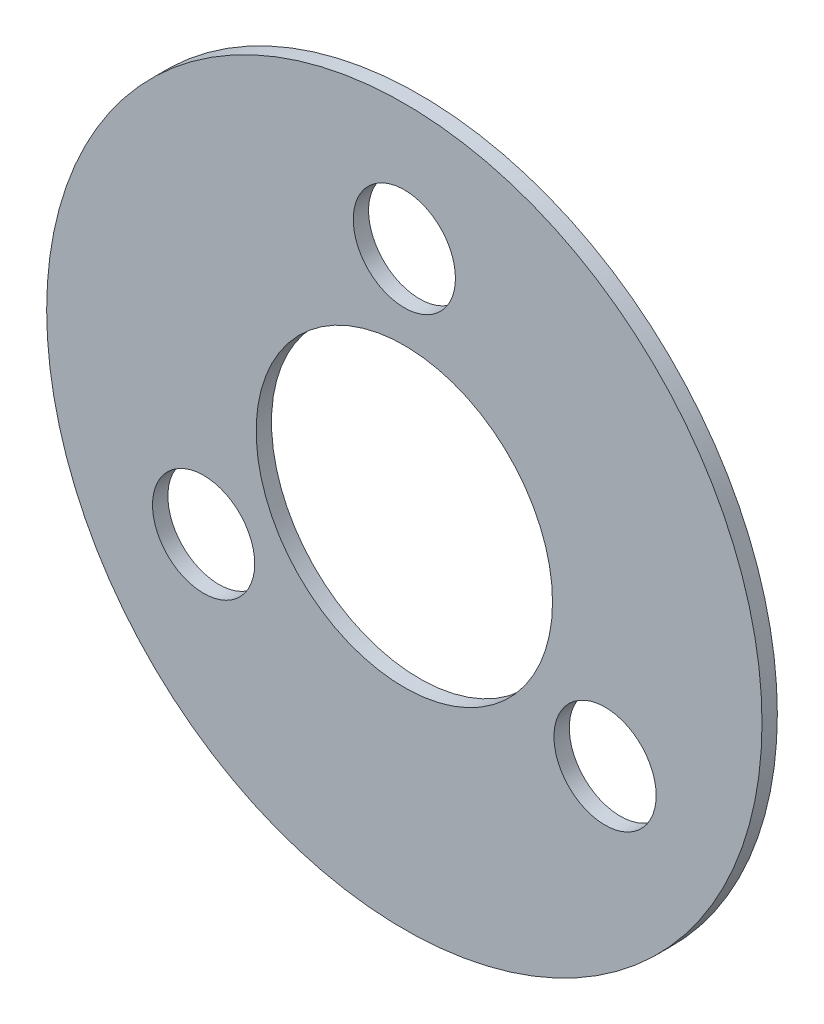
SolidWorks part; units mm, degrees
ref_plane "前视基准面" through (0, 0, 0) normal (0, 0, 1) x (1, 0, 0)
ref_plane "上视基准面" through (0, 0, 0) normal (0, 1, 0) x (1, 0, 0)
ref_plane "右视基准面" through (0, 0, 0) normal (1, 0, 0) x (0, 0, -1)
sketch "草图1" plane through (0, 0, 0) normal (0, 0, 1) x (1, 0, 0)
  circle A0 centre (0, 0) radius 70
  circle A1 centre (0, 0) radius 29
  dimension "D1" = 140
  dimension "D2" = 58
extrude "凸台-拉伸1" add sketch "草图1" along normal blind 3
sketch "草图2" plane through (0, 0, 3) normal (0, 0, 1) x (1, 0, 0)
  circle A0 centre (0, 0) radius 45.357 construction
  circle A1 centre (0, 45.357) radius 10
  circle A2 centre (39.2803, -22.6785) radius 10
  circle A3 centre (-39.2803, -22.6785) radius 10
  point P11 (0, 0)
  dimension "D1" = 90.714
  dimension "D2" = 20
  dimension "D3" = 3
extrude "切除-拉伸1" cut sketch "草图2" against normal blind 3
ref_plane "基准面1" through (0, 0, 0) normal (0, 0, -1) x (-1, 0, 0)
ref_plane "基准面2" through (0, 0, 3) normal (0, 0, 1) x (1, 0, 0)
